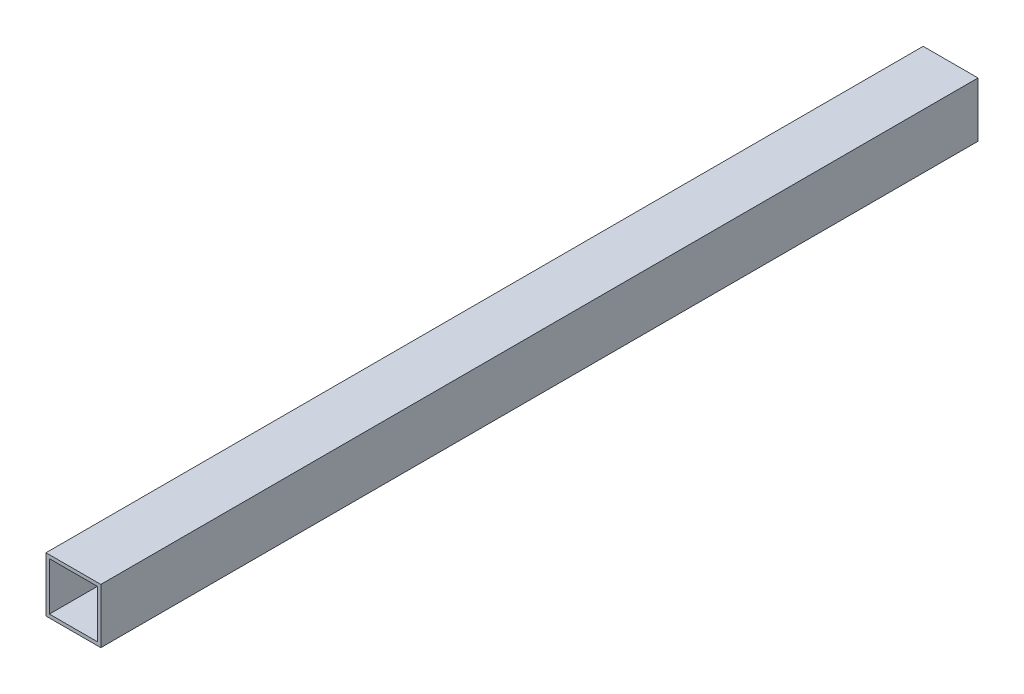
SolidWorks part; units mm, degrees
material "AISI 1020"
ref_plane "Front Plane" through (0, 0, 0) normal (0, 0, 1) x (1, 0, 0)
ref_plane "Top Plane" through (0, 0, 0) normal (0, 1, 0) x (1, 0, 0)
ref_plane "Right Plane" through (0, 0, 0) normal (1, 0, 0) x (0, 0, -1)
sketch "Sketch1" plane through (0, 0, 0) normal (0, 0, 1) x (1, 0, 0)
  line L0 (22.225, 22.225) -> (22.225, 25.4) construction
  line L1 (-25.4, -25.4) -> (25.4, -25.4)
  line L2 (-25.4, -25.4) -> (-25.4, 25.4)
  line L3 (-25.4, 25.4) -> (25.4, 25.4)
  line L4 (25.4, -25.4) -> (25.4, 25.4)
  line L5 (-25.4, -25.4) -> (25.4, 25.4) construction
  line L6 (-25.4, 25.4) -> (25.4, -25.4) construction
  line L7 (-22.225, -22.225) -> (22.225, -22.225)
  line L8 (-22.225, -22.225) -> (-22.225, 22.225)
  line L9 (-22.225, 22.225) -> (22.225, 22.225)
  line L10 (22.225, -22.225) -> (22.225, 22.225)
  line L11 (-22.225, -22.225) -> (22.225, 22.225) construction
  line L12 (-22.225, 22.225) -> (22.225, -22.225) construction
  line L13 (22.225, -22.225) -> (25.4, -22.225) construction
  point P0 (0, 0)
  point P6 (0, 0)
  dimension "D2" = 50.8
  dimension "D3" = 3.175
extrude "Boss-Extrude1" add sketch "Sketch1" along normal blind 812.8
